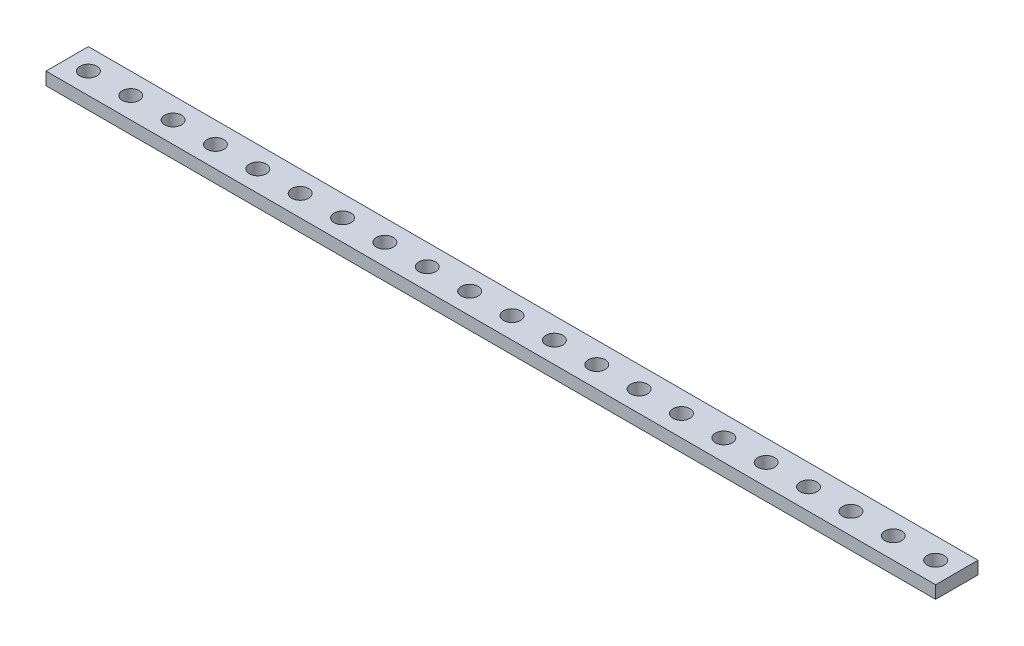
SolidWorks part; units mm, degrees
ref_plane "Plan de face" through (0, 0, 0) normal (0, 0, 1) x (1, 0, 0)
ref_plane "Plan de dessus" through (0, 0, 0) normal (0, 1, 0) x (1, 0, 0)
ref_plane "Plan de droite" through (0, 0, 0) normal (1, 0, 0) x (0, 0, -1)
sketch "Esquisse1" plane through (0, 0, 0) normal (0, 1, 0) x (1, 0, 0)
  line L0 (0, 0) -> (140, 0)
  line L1 (0, 0) -> (-140, 0)
  line L2 (-140, 0) -> (-140, 10)
  line L3 (-140, 10) -> (140, 10)
  line L4 (140, 10) -> (140, 0)
  line L5 (-140, 5) -> (-135, 5) construction
  circle A0 centre (-135, 5) radius 2
  circle A1 centre (-125, 5) radius 2
  circle A2 centre (-115, 5) radius 2
  circle A3 centre (-105, 5) radius 2
  circle A4 centre (-95, 5) radius 2
  circle A5 centre (-85, 5) radius 2
  circle A6 centre (-75, 5) radius 2
  circle A7 centre (-65, 5) radius 2
  circle A8 centre (-55, 5) radius 2
  circle A9 centre (-45, 5) radius 2
  circle A10 centre (-35, 5) radius 2
  circle A11 centre (-25, 5) radius 2
  circle A12 centre (-15, 5) radius 2
  circle A13 centre (-5, 5) radius 2
  circle A14 centre (5, 5) radius 2
  circle A15 centre (15, 5) radius 2
  circle A16 centre (25, 5) radius 2
  circle A17 centre (35, 5) radius 2
  circle A18 centre (45, 5) radius 2
  circle A19 centre (55, 5) radius 2
  circle A20 centre (65, 5) radius 2
  circle A21 centre (75, 5) radius 2
  circle A22 centre (85, 5) radius 2
  circle A23 centre (95, 5) radius 2
  circle A24 centre (105, 5) radius 2
  circle A25 centre (115, 5) radius 2
  circle A26 centre (125, 5) radius 2
  circle A27 centre (135, 5) radius 2
  dimension "D3" = 28
  dimension "D1" = 140
  dimension "D2" = 140
extrude "Boss.-Extru.1" add sketch "Esquisse1" along normal blind 3
sketch "Esquisse2" plane through (0, 3, 0) normal (0, 1, 0) x (1, 0, 0)
  line L0 (-140, 10) -> (70, 10) construction
  line L1 (140, 10) -> (-140, 10) construction
  line L2 (70, 10) -> (70, 0)
  line L3 (-140, 0) -> (140, 0) construction
  line L4 (70, 0) -> (140, 0)
  line L5 (140, 0) -> (140, 10)
  line L6 (140, 10) -> (70, 10)
extrude "Enlèv. mat.-Extru.1" cut sketch "Esquisse2" against normal up to next
